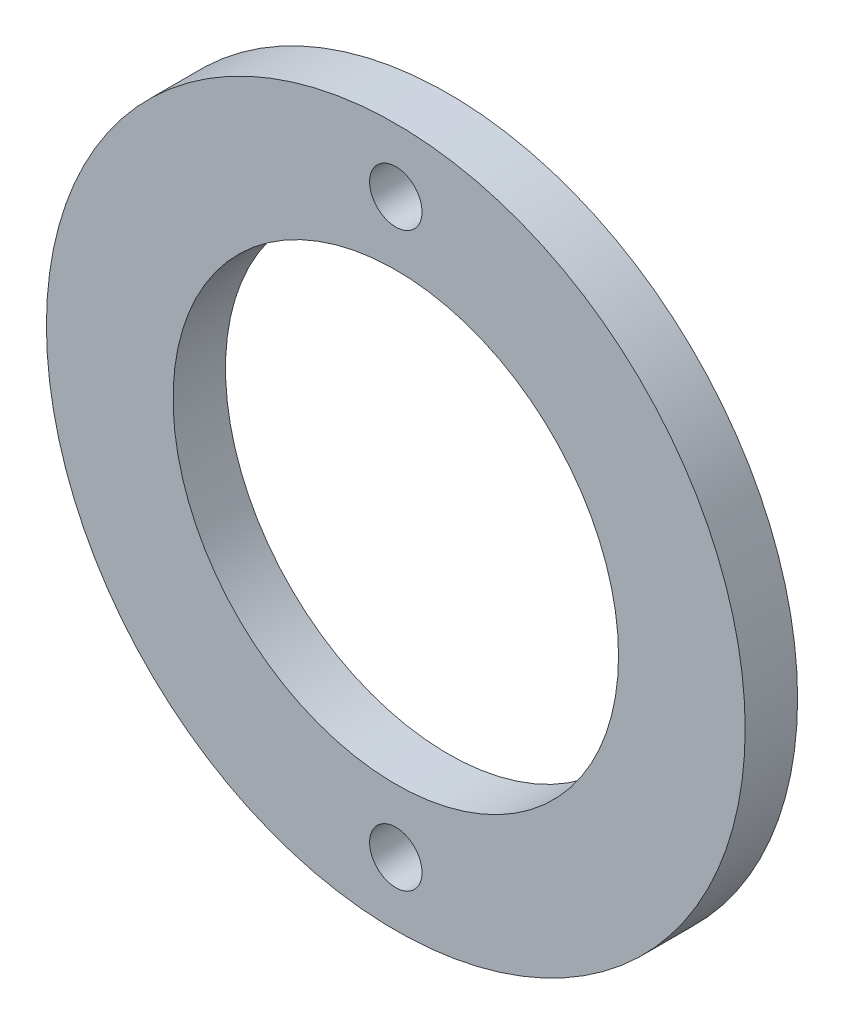
SolidWorks part; units mm, degrees
ref_plane "Front Plane" through (0, 0, 0) normal (0, 0, 1) x (1, 0, 0)
ref_plane "Top Plane" through (0, 0, 0) normal (0, 1, 0) x (1, 0, 0)
ref_plane "Right Plane" through (0, 0, 0) normal (1, 0, 0) x (0, 0, -1)
sketch "Sketch1" plane through (0, 0, 0) normal (0, 0, 1) x (1, 0, 0)
  circle A0 centre (0, 0) radius 12.75
  circle A1 centre (0, 0) radius 20
  point P4 (0, 0)
  dimension "D1" = 25.5
  dimension "D2" = 40
extrude "Boss-Extrude1" add sketch "Sketch1" along normal blind 3
hole_wizard "Ø3.0mm Dowel Hole1" positions "Sketch2" profile "Sketch3" hole size "Ø3.0" standard "ANSI Metric" end condition through all
sketch "Sketch2" plane through (0, 0, 3) normal (0, 0, 1) x (1, 0, 0)
  point P0 (0, 16.375)
  point P2 (0, -16.375)
  point P6 (0, 0)
  dimension "D1" = 16.375
  dimension "D2" = 16.375
sketch "Sketch3" plane through (0, 16.375, 3) normal (1, 0, 0) x (0, -1, 0)
  line L0 (0, 0) -> (0, 3)
  line L1 (0, 3) -> (1.5, 3)
  line L2 (1.5, 3) -> (1.5, 0)
  line L5 (1.5, 0) -> (0, 0)
  line L11 (0, -6.35) -> (0, 107.95) construction
  dimension "Thru Hole Dia." = 3
  dimension "Thru Hole Depth" = 3
equation "\"D2@Sketch2\"=\"D1@Sketch2\""
